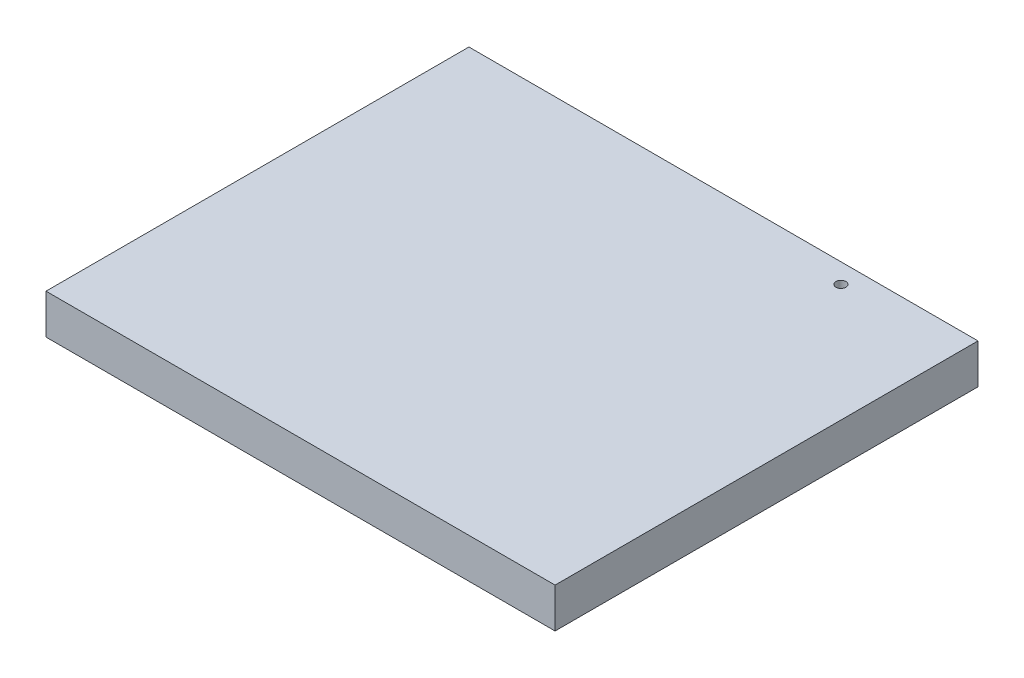
SolidWorks part; units mm, degrees
ref_plane "Front Plane" through (0, 0, 0) normal (0, 0, 1) x (1, 0, 0)
ref_plane "Top Plane" through (0, 0, 0) normal (0, 1, 0) x (1, 0, 0)
ref_plane "Right Plane" through (0, 0, 0) normal (1, 0, 0) x (0, 0, -1)
sketch "Sketch2" plane through (0, 0, 0) normal (0, 1, 0) x (1, 0, 0)
  line L1 (-145.7944, 109.8836) -> (179.2056, 109.8836)
  line L2 (-145.7944, 109.8836) -> (-145.7944, -160.1164)
  line L3 (-145.7944, -160.1164) -> (179.2056, -160.1164)
  line L4 (179.2056, 109.8836) -> (179.2056, -160.1164)
extrude "Boss-Extrude1" add sketch "Sketch2" along normal blind 25.4
sketch "Sketch6" plane through (0, 25.4, 0) normal (0, 1, 0) x (1, 0, 0)
  circle A2 centre (104.2056, 97.3836) radius 3.2
extrude "Cut-Extrude3" cut sketch "Sketch6" against normal blind 25.4
